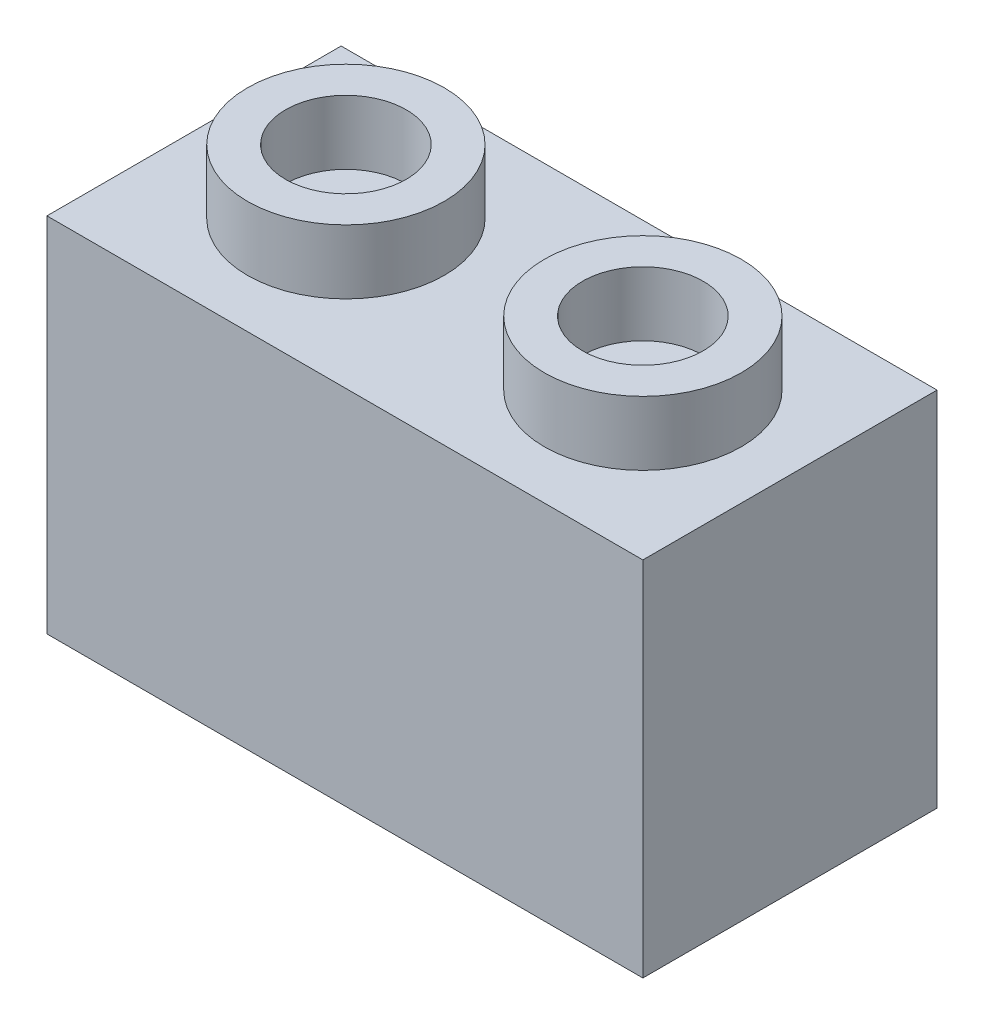
SolidWorks part; units mm, degrees
ref_plane "Спереди" through (0, 0, 0) normal (0, 0, 1) x (1, 0, 0)
ref_plane "Сверху" through (0, 0, 0) normal (0, 1, 0) x (1, 0, 0)
ref_plane "Справа" through (0, 0, 0) normal (1, 0, 0) x (0, 0, -1)
sketch "Эскиз2" plane through (0, 0, 0) normal (0, 1, 0) x (1, 0, 0)
  line L1 (7.9, -3.9) -> (-7.9, -3.9)
  line L2 (7.9, -3.9) -> (7.9, 3.9)
  line L3 (7.9, 3.9) -> (-7.9, 3.9)
  line L4 (-7.9, -3.9) -> (-7.9, 3.9)
  line L5 (7.9, -3.9) -> (-7.9, 3.9) construction
  line L6 (7.9, 3.9) -> (-7.9, -3.9) construction
  point P1 (0, 0)
  dimension "D1" = 15.8
  dimension "D2" = 7.8
extrude "Бобышка-Вытянуть1" add sketch "Эскиз2" along normal blind 9.6
sketch "Эскиз3" plane through (0, 9.6, 0) normal (0, 1, 0) x (1, 0, 0)
  line L0 (-7.9, -3.9) -> (7.9, -3.9) construction
  line L3 (7.9, -3.9) -> (7.9, 3.9) construction
  circle A0 centre (4, 0) radius 2.6094
  circle A1 centre (-3.874, 0) radius 2.6094
  dimension "D1" = 3.9
  dimension "D2" = 3.9
  dimension "D3" = 2
extrude "Бобышка-Вытянуть2" add sketch "Эскиз3" along normal blind 1.7
sketch "Эскиз4" plane through (0, 11.3, 0) normal (0, 1, 0) x (1, 0, 0)
  circle A0 centre (-3.874, 0) radius 1.6
extrude "Вырез-Вытянуть1" cut sketch "Эскиз4" against normal blind 1.7
sketch "Эскиз5" plane through (0, 11.3, 0) normal (0, 1, 0) x (1, 0, 0)
  circle A0 centre (4, 0) radius 1.6
extrude "Вырез-Вытянуть2" cut sketch "Эскиз5" against normal blind 1.7
